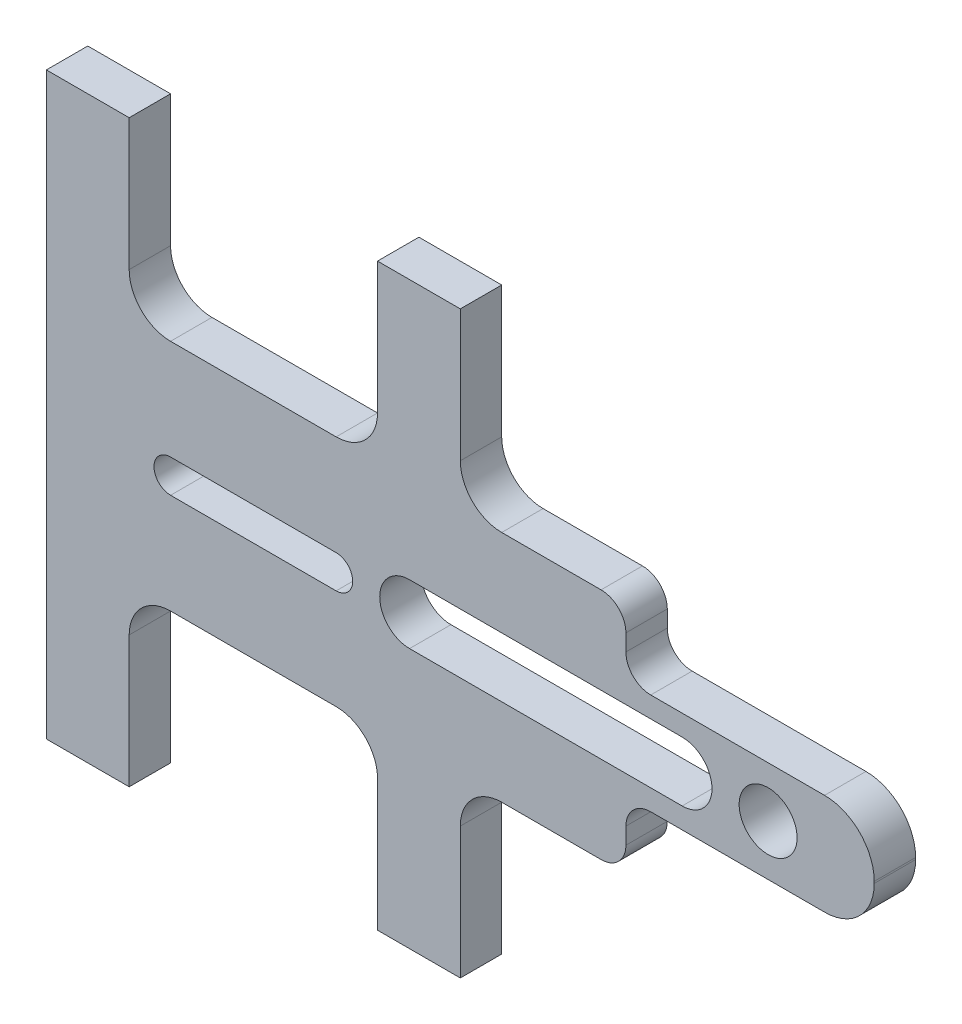
SolidWorks part; units mm, degrees
ref_plane "Front Plane" through (0, 0, 0) normal (0, 0, 1) x (1, 0, 0)
ref_plane "Top Plane" through (0, 0, 0) normal (0, 1, 0) x (1, 0, 0)
ref_plane "Right Plane" through (0, 0, 0) normal (1, 0, 0) x (0, 0, -1)
sketch "Sketch1" plane through (0, 0, 0) normal (0, 0, 1) x (1, 0, 0)
  line L0 (0, -17.5) -> (0, 17.5)
  line L2 (50, -0.0548) -> (50, 0.0548)
  line L4 (0, -17.5) -> (5, -17.5)
  line L5 (27.5, -7.0548) -> (33.5016, -7.0548)
  line L6 (20, -17.5) -> (25, -17.5)
  line L8 (21.9351, 0) -> (38.3996, 0) construction
  line L11 (5, -17.5) -> (5, -9.5548)
  line L12 (7.5, -7.0548) -> (17.5, -7.0548)
  line L13 (20, -9.5548) -> (20, -17.5)
  line L14 (25, -17.5) -> (25, -9.5548)
  line L15 (35.0016, -5.5548) -> (35.0016, -4.5548)
  line L16 (36.5016, -3.0548) -> (47, -3.0548)
  line L17 (36.5016, 3.0548) -> (47, 3.0548)
  line L18 (35.0016, 5.5548) -> (35.0016, 4.5548)
  line L19 (27.5, 7.0548) -> (33.5016, 7.0548)
  line L20 (20, 17.5) -> (25, 17.5)
  line L21 (25, 17.5) -> (25, 9.5548)
  line L22 (20, 9.5548) -> (20, 17.5)
  line L23 (5, 17.5) -> (5, 9.5548)
  line L24 (7.5, 7.0548) -> (17.5, 7.0548)
  line L25 (0, 17.5) -> (5, 17.5)
  line L26 (7.5, 0) -> (17.5, 0) construction
  line L27 (7.5, 1) -> (17.5, 1)
  line L28 (7.5, -1) -> (17.5, -1)
  line L29 (21.9351, 1.8014) -> (38.3996, 1.8014)
  line L30 (21.9351, -1.8014) -> (38.3996, -1.8014)
  arc A2 (27.5, 7.0548) -> (25, 9.5548) centre (27.5, 9.5548) cw
  arc A3 (27.5, -7.0548) -> (25, -9.5548) centre (27.5, -9.5548) ccw
  arc A4 (17.5, -7.0548) -> (20, -9.5548) centre (17.5, -9.5548) cw
  arc A5 (7.5, -7.0548) -> (5, -9.5548) centre (7.5, -9.5548) ccw
  arc A6 (20, 9.5548) -> (17.5, 7.0548) centre (17.5, 9.5548) cw
  arc A7 (7.5, 7.0548) -> (5, 9.5548) centre (7.5, 9.5548) cw
  arc A8 (35.0016, -5.5548) -> (33.5016, -7.0548) centre (33.5016, -5.5548) cw
  arc A9 (35.0016, -4.5548) -> (36.5016, -3.0548) centre (36.5016, -4.5548) cw
  arc A10 (36.5016, 3.0548) -> (35.0016, 4.5548) centre (36.5016, 4.5548) cw
  arc A11 (35.0016, 5.5548) -> (33.5016, 7.0548) centre (33.5016, 5.5548) ccw
  arc A12 (50, -0.0548) -> (47, -3.0548) centre (47, -0.0548) cw
  arc A13 (50, 0.0548) -> (47, 3.0548) centre (47, 0.0548) ccw
  circle A14 centre (43.5916, 0) radius 1.75
  arc A15 (7.5, 1) -> (7.5, -1) centre (7.5, 0) ccw
  arc A16 (17.5, -1) -> (17.5, 1) centre (17.5, 0) ccw
  arc A17 (21.9351, 1.8014) -> (21.9351, -1.8014) centre (21.9351, 0) ccw
  arc A18 (38.3996, -1.8014) -> (38.3996, 1.8014) centre (38.3996, 0) ccw
  point P14 (12.5, 0)
  point P34 (25, 7.0548)
  point P37 (25, -7.0548)
  point P40 (20, -7.0548)
  point P43 (5, -7.0548)
  point P46 (20, 7.0548)
  point P49 (5, 7.0548)
  point P52 (35.0016, -7.0548)
  point P55 (35.0016, -3.0548)
  point P58 (35.0016, 3.0548)
  point P61 (35.0016, 7.0548)
  point P66 (30.1673, 0)
  dimension "D1" = 2.5
  dimension "D2" = 1.5
  dimension "D3" = 3
extrude "Boss-Extrude1" add sketch "Sketch1" along normal blind 2.5
